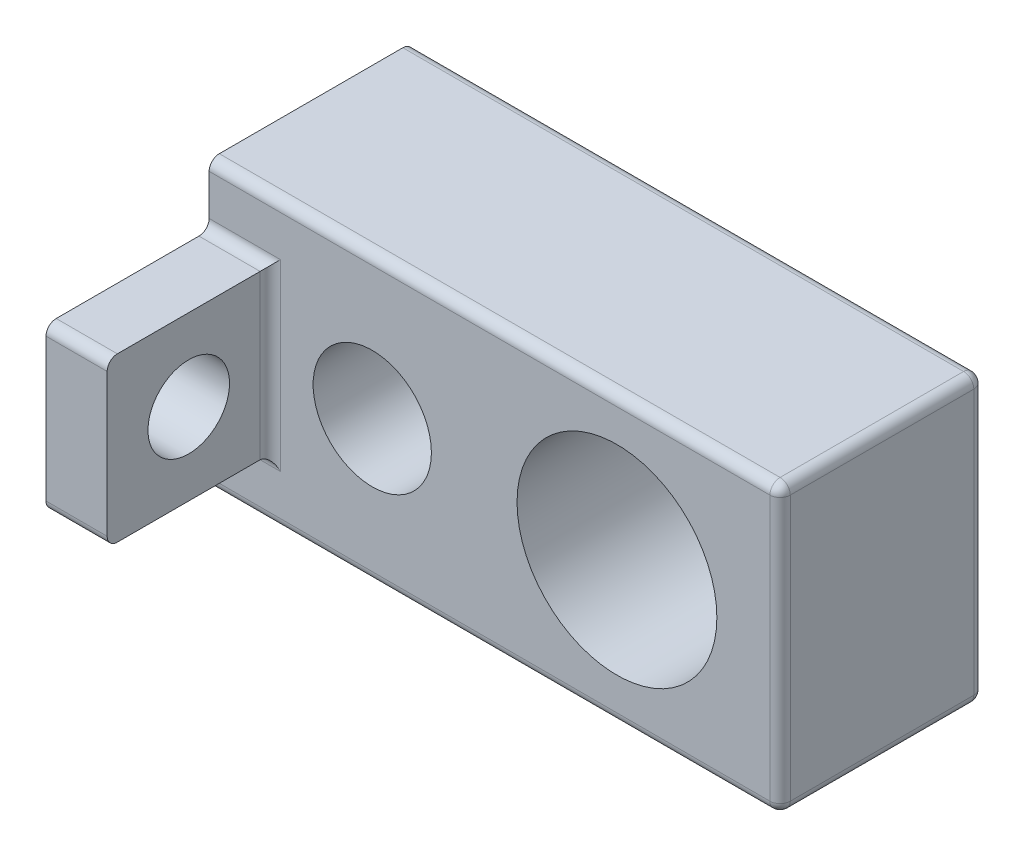
SolidWorks part; units mm, degrees
ref_plane "Front Plane" through (0, 0, 0) normal (0, 0, 1) x (1, 0, 0)
ref_plane "Top Plane" through (0, 0, 0) normal (0, 1, 0) x (1, 0, 0)
ref_plane "Right Plane" through (0, 0, 0) normal (1, 0, 0) x (0, 0, -1)
sketch "Sketch1" plane through (0, 0, 0) normal (0, 0, 1) x (1, 0, 0)
  line L1 (7, -3.5) -> (-7, -3.5)
  line L2 (7, -3.5) -> (7, 3.5)
  line L3 (7, 3.5) -> (-7, 3.5)
  line L4 (-7, -3.5) -> (-7, 3.5)
  line L5 (7, -3.5) -> (-7, 3.5) construction
  line L6 (7, 3.5) -> (-7, -3.5) construction
  point P0 (0, 0)
  dimension "D1" = 14
  dimension "D2" = 7
extrude "Boss-Extrude1" add sketch "Sketch1" along normal blind 5
sketch "Sketch2" plane through (0, 0, 0) normal (0, 0, 1) x (1, 0, 0)
  line L0 (3, 0) -> (-3, 0) construction
  line L1 (3, 0) -> (7, 0) construction
  line L2 (7, -3.5) -> (7, 3.5) construction
  line L3 (-3, 0) -> (-7, 0) construction
  line L4 (-7, 3.5) -> (-7, -3.5) construction
  circle A0 centre (3, 0) radius 2.45
  circle A1 centre (-3, 0) radius 1.45
  dimension "D1" = 4.9
  dimension "D2" = 2.9
  dimension "D3" = 4
  dimension "D4" = 4
extrude "Cut-Extrude1" cut sketch "Sketch2" along normal through all
sketch "Sketch5" plane through (-7, 0, 0) normal (-1, 0, 0) x (0, 0, 1)
  line L0 (5, 3.5) -> (5, -3.5) construction
  line L1 (5, -2) -> (9, -2)
  line L2 (5, -2) -> (5, 2)
  line L3 (5, 2) -> (9, 2)
  line L4 (9, -2) -> (9, 2)
  point P6 (5, 0)
  dimension "D1" = 4
  dimension "D2" = 4
extrude "Boss-Extrude3" add sketch "Sketch5" against normal blind 1.5
sketch "Sketch9" plane through (-5.5, 0, 0) normal (1, 0, 0) x (0, 0, -1)
  line L0 (-9, 2) -> (-5, -2) construction
  line L1 (-5, -2) -> (-9, -2) construction
  line L2 (-9, -2) -> (-5, 2) construction
  circle A0 centre (-7, 0) radius 1
  dimension "D1" = 2
extrude "Cut-Extrude2" cut sketch "Sketch9" against normal blind 2
fillet "Fillet1" radius 0.25 13 edges at (-5.5, 0, 5) (-6.25, 2, 5) (-6.25, -2, 5) (0, -3.5, 0) (0, -3.5, 5) (7, -3.5, 2.5) (7, 0, 5) (7, 0, 0) (7, 3.5, 2.5) (0, 3.5, 0) (-6.25, -2, 9) (-6.25, 2, 9) (0, 3.5, 5)
